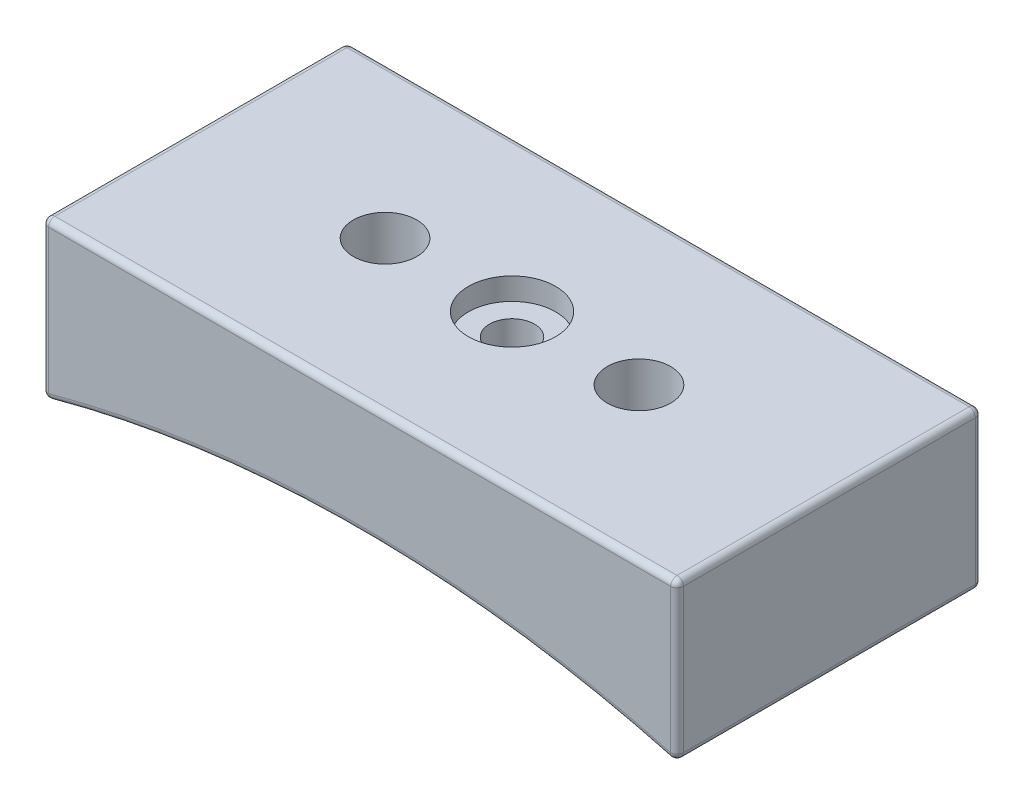
SolidWorks part; units mm, degrees
ref_plane "Front Plane" through (0, 0, 0) normal (0, 0, 1) x (1, 0, 0)
ref_plane "Top Plane" through (0, 0, 0) normal (0, 1, 0) x (1, 0, 0)
ref_plane "Right Plane" through (0, 0, 0) normal (1, 0, 0) x (0, 0, -1)
sketch "Sketch1" plane through (0, 0, 0) normal (0, 0, 1) x (1, 0, 0)
  line L0 (0, 0) -> (0, 21.7025) construction
  line L1 (-31.75, 12.7) -> (31.75, 12.7)
  line L2 (-31.75, 12.7) -> (-31.75, -3.175)
  line L4 (31.75, 12.7) -> (31.75, -3.175)
  line L5 (-31.75, 12.7) -> (31.75, -3.175) construction
  line L6 (-31.75, -3.175) -> (31.75, 12.7) construction
  arc A0 (-31.75, -3.175) -> (31.75, -3.175) centre (0, -117.0694) cw
  point P0 (0, 4.7625)
  point P9 (0, 12.7)
  point P10 (0, 17.0011)
  dimension "D3" = 118.237
  dimension "D1" = 63.5
  dimension "D2" = 15.875
extrude "Boss-Extrude1" add sketch "Sketch1" along normal blind 30.48
hole_wizard "CBORE for #8 Button Head Cap Screw1" positions "Sketch2" profile "Sketch3" counterbore size "#8" standard "ANSI Inch" end condition through all
sketch "Sketch2" plane through (0, 12.7, 0) normal (0, 1, 0) x (1, 0, 0)
  line L0 (-31.75, 0) -> (31.75, -30.48) construction
  point P6 (0, -15.24)
sketch "Sketch3" plane through (0, 12.7, 15.24) normal (1, 0, 0) x (0, 0, 1)
  line L0 (0, 0) -> (0, 15.875)
  line L1 (0, 15.875) -> (2.2479, 15.875)
  line L3 (2.2479, 15.875) -> (2.2479, 2.2098)
  line L4 (2.2479, 2.2098) -> (4.3663, 2.2098)
  line L5 (4.3663, 2.2098) -> (4.3663, 0)
  line L7 (4.3663, 0) -> (0, 0)
  line L11 (0, -6.35) -> (0, 107.95) construction
  dimension "Thru Hole Dia." = 4.4958
  dimension "Thru Hole Depth" = 15.875
  dimension "C'Bore Dia." = 8.7325
  dimension "C'Bore Depth" = 2.2098
ref_plane "Plane2" through (0, 0, 0) normal (1, 0, 0) x (0, 0, -1)
ref_plane "Plane4" through (0, 0, 15.24) normal (0, 0, -1) x (-1, 0, 0)
ref_plane "Plane5" through (0, 1.1676, 0) normal (0, -1, 0) x (-1, 0, 0)
sketch "Sketch6" plane through (0, 1.1676, 0) normal (0, -1, 0) x (-1, 0, 0)
  line L0 (7.9238, -15.24) -> (-7.9238, -15.24) construction
  line L1 (0, 7.9238) -> (0, -7.9238) construction
  line L2 (0, -15.24) -> (0, -37.3295) construction
  circle A0 centre (12.7, -15.24) radius 3.175
  circle A1 centre (-12.7, -15.24) radius 3.175
  dimension "D1" = 6.35
  dimension "D2" = 12.7
extrude "Cut-Extrude1" cut sketch "Sketch6" against normal through all both and the other way through all
sketch "Sketch7" plane through (0, 1.1676, 0) normal (0, -1, 0) x (-1, 0, 0)
  line L0 (0, -15.24) -> (0, -35.0411) construction
  circle A0 centre (12.7, -15.24) radius 8.128
  circle A1 centre (-12.7, -15.24) radius 8.128
  dimension "D1" = 16.256
extrude "Cut-Extrude2" cut sketch "Sketch7" against normal blind 5.588 and the other way through all
fillet "Fillet1" radius 0.635 12 edges at (0, 12.7, 0) (0, 1.1676, 0) (-31.75, 12.7, 15.24) (-31.75, -3.175, 15.24) (-31.75, 4.7625, 0) (-31.75, 4.7625, 30.48) (0, 12.7, 30.48) (0, 1.1676, 30.48) (31.75, -3.175, 15.24) (31.75, 4.7625, 30.48) (31.75, 12.7, 15.24) (31.75, 4.7625, 0)
